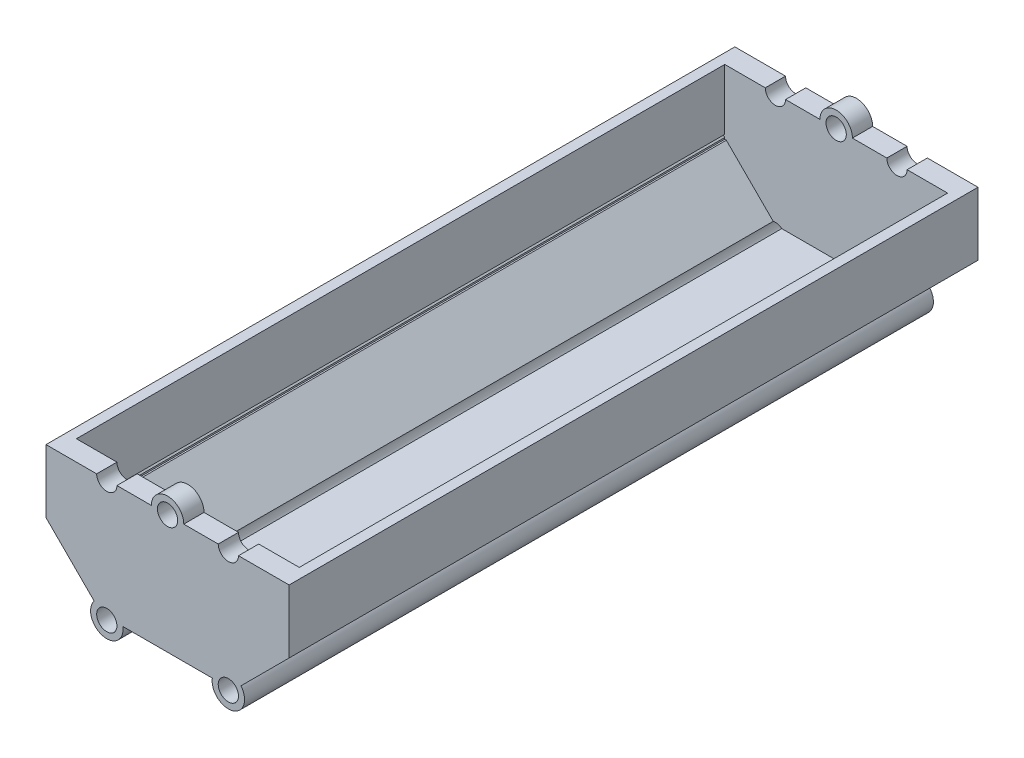
SolidWorks part; units mm, degrees
ref_plane "Front Plane" through (0, 0, 0) normal (0, 0, 1) x (1, 0, 0)
ref_plane "Top Plane" through (0, 0, 0) normal (0, 1, 0) x (1, 0, 0)
ref_plane "Right Plane" through (0, 0, 0) normal (1, 0, 0) x (0, 0, -1)
sketch "Sketch1" plane through (0, 0, 0) normal (0, 0, 1) x (1, 0, 0)
  line L0 (-61.2213, -5.6812) -> (-61.2213, 33.9739)
  line L2 (-61.2213, -5.6812) -> (-31.0408, -35.8616)
  line L4 (91.1787, -5.6812) -> (60.9983, -35.8616)
  line L5 (-61.2213, 33.9739) -> (-29.4713, 33.9739)
  line L6 (91.1787, 33.9739) -> (91.1787, -5.6812)
  line L7 (-16.7713, 33.9739) -> (4.8187, 33.9739)
  line L8 (59.4287, 33.9739) -> (91.1787, 33.9739)
  line L9 (25.1387, 33.9739) -> (46.7287, 33.9739)
  line L10 (-13.081, -40.671) -> (43.0384, -40.671)
  circle A0 centre (14.9787, 33.9739) radius 6.35
  arc A1 (46.7287, 33.9739) -> (59.4287, 33.9739) centre (53.0787, 33.9739) ccw
  arc A2 (-29.4713, 33.9739) -> (-16.7713, 33.9739) centre (-23.1213, 33.9739) ccw
  circle A3 centre (53.0787, -42.2261) radius 6.35
  circle A4 centre (-23.1213, -42.2261) radius 6.35
  arc A5 (25.1387, 33.9739) -> (4.8187, 33.9739) centre (14.9787, 33.9739) ccw
  arc A6 (43.0384, -40.671) -> (60.9983, -35.8616) centre (53.0787, -42.2261) ccw
  arc A7 (-31.0408, -35.8616) -> (-13.081, -40.671) centre (-23.1213, -42.2261) ccw
  dimension "D1" = 76.2
  dimension "D2" = 76.2
  dimension "D7" = 38.1
  dimension "D8" = 38.1
  dimension "D9" = 76.2
  dimension "D10" = 38.1
extrude "Boss-Extrude1" add sketch "Sketch1" along normal blind 431.8
sketch "Sketch2" plane through (0, 33.9739, 0) normal (0, 1, 0) x (1, 0, 0)
  line L0 (-29.4713, -431.8) -> (-61.2213, -431.8) construction
  line L1 (84.8287, -419.1) -> (-54.8713, -419.1)
  line L2 (84.8287, -419.1) -> (84.8287, -12.7)
  line L3 (84.8287, -12.7) -> (-54.8713, -12.7)
  line L4 (-54.8713, -419.1) -> (-54.8713, -12.7)
  line L5 (-61.2213, -431.8) -> (-61.2213, 0) construction
  dimension "D1" = 406.4
  dimension "D2" = 12.7
  dimension "D3" = 139.7
  dimension "D4" = 6.35
extrude "Cut-Extrude1" cut sketch "Sketch2" against normal blind 40.64 and the other way blind 12.7
sketch "Sketch3" plane through (0, 0, 0) normal (0, 0, -1) x (-1, 0, 0)
  line L1 (-85.7781, -4.0075) -> (56.55, -4.0075)
  line L2 (-85.7781, -4.0075) -> (-53.0667, -37.2967)
  line L3 (-53.0667, -37.2967) -> (23.2021, -37.2967)
  line L4 (56.55, -4.0075) -> (23.2021, -37.2967)
extrude "Cut-Extrude2" cut sketch "Sketch3" along direction (0, 0, 1) on the side against the normal blind 406.4 from offset 12.7 offset against normal yes
